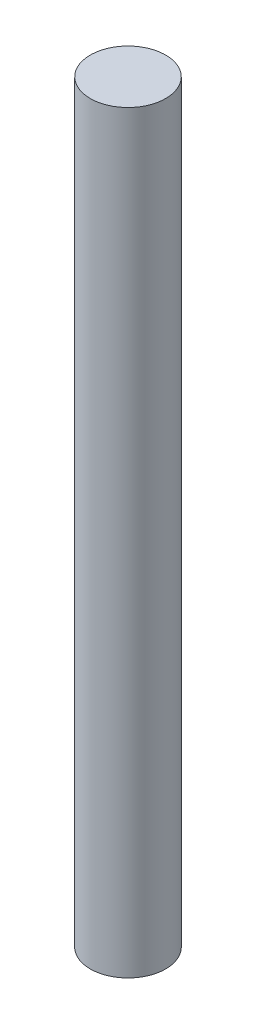
SolidWorks part; units mm, degrees
material "Stainless Steel (ferritic)"
ref_plane "Front Plane" through (0, 0, 0) normal (0, 0, 1) x (1, 0, 0)
ref_plane "Top Plane" through (0, 0, 0) normal (0, 1, 0) x (1, 0, 0)
ref_plane "Right Plane" through (0, 0, 0) normal (1, 0, 0) x (0, 0, -1)
sketch "Sketch1" plane through (0, 0, 0) normal (0, 1, 0) x (1, 0, 0)
  circle A0 centre (0, 0) radius 1.5
  dimension "D1" = 3
extrude "Boss-Extrude1" add sketch "Sketch1" along normal blind 30
equation "\"Pin_Length\"= 30"
equation "\"D1@Boss-Extrude1\"= \"Pin_Length\""
